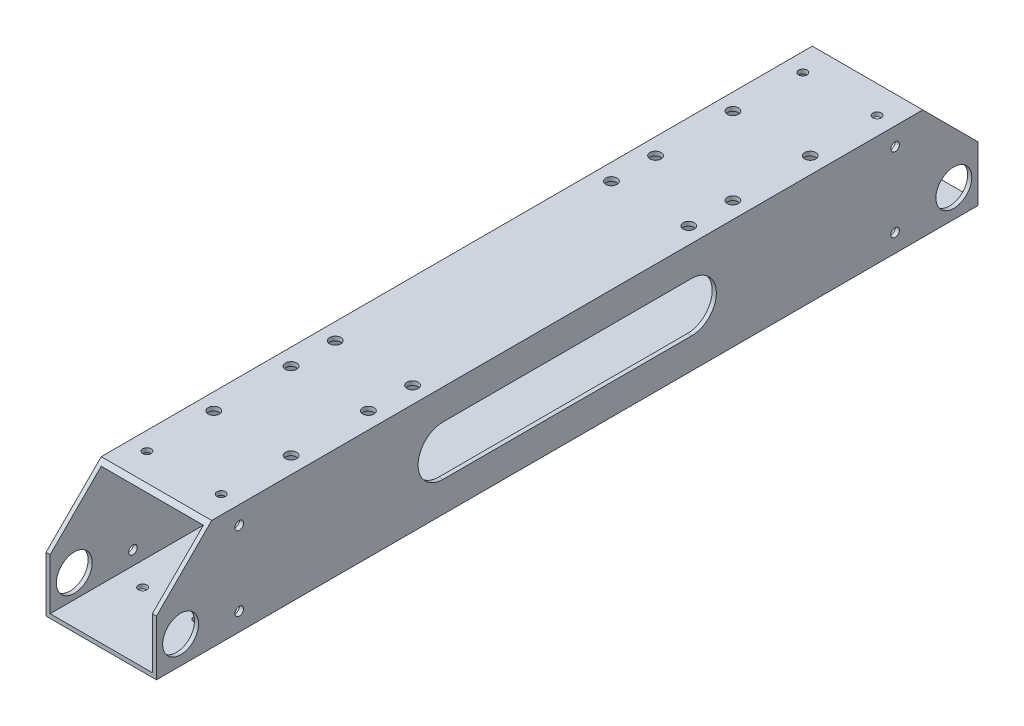
SolidWorks part; units mm, degrees
material "1060 合金"
ref_plane "前视基准面" through (0, 0, 0) normal (0, 0, 1) x (1, 0, 0)
ref_plane "上视基准面" through (0, 0, 0) normal (0, 1, 0) x (1, 0, 0)
ref_plane "右视基准面" through (0, 0, 0) normal (1, 0, 0) x (0, 0, -1)
other "Configuration Table"
sketch "草图1" plane through (0, 0, 0) normal (0, 0, 1) x (1, 0, 0)
  line L0 (-20, 20) -> (-20, -20)
  line L1 (-18.5, 18.5) -> (18.5, 18.5)
  line L2 (-18.5, 18.5) -> (-18.5, -18.5)
  line L3 (-18.5, -18.5) -> (18.5, -18.5)
  line L4 (18.5, 18.5) -> (18.5, -18.5)
  line L5 (-18.5, 18.5) -> (18.5, -18.5) construction
  line L6 (-18.5, -18.5) -> (18.5, 18.5) construction
  line L7 (-20, -20) -> (20, -20)
  line L8 (20, 20) -> (20, -20)
  line L9 (-20, 20) -> (20, 20)
  point P0 (0, 0)
  dimension "D1" = 1.5
  dimension "D2" = 40
extrude "凸台-拉伸1" add sketch "草图1" along normal mid plane 297.5
sketch "草图2" plane through (20, 0, 0) normal (1, 0, 0) x (0, 0, -1)
  line L0 (-140, -10) -> (140, -10) construction
  line L1 (-148.75, 0) -> (-128.75, 20)
  line L2 (0, 0) -> (0, -10) construction
  line L4 (-148.75, -20) -> (-148.75, 20) construction
  line L5 (-148.75, 20) -> (148.75, 20) construction
  line L6 (-128.75, 20) -> (-148.75, 20)
  line L7 (-148.75, 20) -> (-148.75, 0)
  line L11 (0, -7.5) -> (0, -50007.5) construction
  line L12 (-45, 0) -> (45, 0) construction
  line L13 (-45, 9) -> (45, 9)
  line L14 (-45, -9) -> (45, -9)
  line L15 (128.75, 20) -> (148.75, 20)
  line L16 (148.75, 0) -> (128.75, 20)
  line L17 (148.75, 20) -> (148.75, 0)
  circle A0 centre (-140, -10) radius 6.5
  circle A1 centre (140, -10) radius 6.5
  arc A2 (-45, 9) -> (-45, -9) centre (-45, 0) ccw
  arc A3 (45, -9) -> (45, 9) centre (45, 0) ccw
  point P25 (0, 0)
  dimension "D1" = 280
  dimension "D2" = 13
  dimension "D6" = 9
  dimension "D3" = 30
  dimension "D4" = 20
  dimension "D5" = 90
extrude "切除-拉伸1" cut sketch "草图2" against normal blind 45
sketch "草图3" plane through (0, 20, 0) normal (0, 1, 0) x (1, 0, 0)
  line L0 (20, -128.75) -> (20, 128.75) construction
  line L1 (-14, -50) -> (14, -50) construction
  line L2 (-14, -50) -> (-14, 50) construction
  line L3 (-14, 50) -> (14, 50) construction
  line L4 (14, -50) -> (14, 50) construction
  line L5 (-14, -50) -> (14, 50) construction
  line L6 (-14, 50) -> (14, -50) construction
  circle A0 centre (-14, 50) radius 2.025
  circle A1 centre (14, 50) radius 2.025
  circle A2 centre (14, -50) radius 2.025
  circle A3 centre (-14, -50) radius 2.025
  point P0 (0, 0)
  dimension "D1" = 4.05
  dimension "D2" = 6
  dimension "D3" = 100
extrude "切除-拉伸2" cut sketch "草图3" against normal blind 50
sketch "草图4" plane through (0, -20, 0) normal (0, -1, 0) x (1, 0, 0)
  circle A0 centre (-14, 50) radius 3.75
  circle A1 centre (14, 50) radius 3.75
  circle A2 centre (-14, -50) radius 3.75
  circle A3 centre (14, -50) radius 3.75
  dimension "D1" = 7.5
extrude "切除-拉伸3" cut sketch "草图4" against normal blind 3
sketch "草图5" plane through (0, 20, 0) normal (0, 1, 0) x (1, 0, 0)
  line L0 (0, 0) -> (0, -50000) construction
  line L2 (-14, 66) -> (14, 66) construction
  line L3 (-14, 66) -> (-14, 94) construction
  line L4 (-14, 94) -> (14, 94) construction
  line L5 (14, 66) -> (14, 94) construction
  line L6 (-14, 66) -> (14, 94) construction
  line L7 (-14, 94) -> (14, 66) construction
  circle A1 centre (-14, 94) radius 2.025
  circle A2 centre (14, 94) radius 2.025
  circle A3 centre (14, 66) radius 2.025
  circle A4 centre (-14, 66) radius 2.025
  point P3 (0, 80)
  dimension "D4" = 4.05
  dimension "D1" = 28
  dimension "D2" = 28
  dimension "D3" = 80
extrude "切除-拉伸4" cut sketch "草图5" against normal blind 60
sketch "草图6" plane through (0, -20, 0) normal (0, -1, 0) x (1, 0, 0)
  circle A0 centre (-14, -66) radius 3.75
  circle A1 centre (14, -66) radius 3.75
  circle A2 centre (-14, -94) radius 3.75
  circle A3 centre (14, -94) radius 3.75
  dimension "D1" = 7.5
extrude "切除-拉伸5" cut sketch "草图6" against normal blind 3
mirror "镜向1" about plane through (0, 0, 0) normal (0, 0, 1) of "切除-拉伸5", "切除-拉伸4"
sketch "草图7" plane through (-20, 0, 0) normal (-1, 0, 0) x (0, 0, 1)
  line L0 (-128.75, 20) -> (-128.75, -20) construction
  line L1 (148.75, -20) -> (-148.75, -20) construction
  line L2 (-122.75, 0) -> (49877.25, 0) construction
  line L3 (-118.75, 13.45) -> (-118.75, -13.45) construction
  line L4 (-148.75, 0) -> (-148.75, -20) construction
  circle A0 centre (-118.75, 13.45) radius 1.55
  circle A1 centre (-118.75, -13.45) radius 1.55
  point P7 (-128.75, 0)
  point P15 (-118.75, 0)
  dimension "D1" = 26.9
  dimension "D3" = 3.1
  dimension "D2" = 30
extrude "切除-拉伸6" cut sketch "草图7" against normal blind 55
sketch "草图8" plane through (0, 20, 0) normal (0, 1, 0) x (1, 0, 0)
  line L0 (-20, 118.75) -> (20, 118.75) construction
  line L1 (-20, -128.75) -> (-20, 128.75) construction
  line L2 (20, -128.75) -> (20, 128.75) construction
  line L3 (-18.5, 148.75) -> (18.5, 148.75) construction
  line L4 (0, 117.75) -> (0, -49882.25) construction
  circle A0 centre (-13.45, 118.75) radius 1.525
  circle A1 centre (13.45, 118.75) radius 1.525
  point P14 (0, 118.75)
  dimension "D2" = 26.9
  dimension "D3" = 3.05
  dimension "D1" = 30
extrude "切除-拉伸7" cut sketch "草图8" against normal blind 20
mirror "镜向2" about plane through (0, 0, 0) normal (0, 0, 1) of "切除-拉伸7", "切除-拉伸6"
sketch "草图9" plane through (0, -20, 0) normal (0, -1, 0) x (1, 0, 0)
  line L0 (0, 0) -> (0, -50000) construction
  line L1 (-10, -123.75) -> (10, -123.75) construction
  line L2 (-20, -148.75) -> (20, -148.75) construction
  line L3 (0, 0) -> (50000, 0) construction
  circle A0 centre (-10, -123.75) radius 1.525
  circle A1 centre (10, -123.75) radius 1.525
  circle A2 centre (10, 123.75) radius 1.525
  circle A3 centre (-10, 123.75) radius 1.525
  point P6 (0, -123.75)
  dimension "D1" = 3.05
  dimension "D2" = 20
  dimension "D3" = 25
extrude "切除-拉伸8" cut sketch "草图9" against normal blind 3
